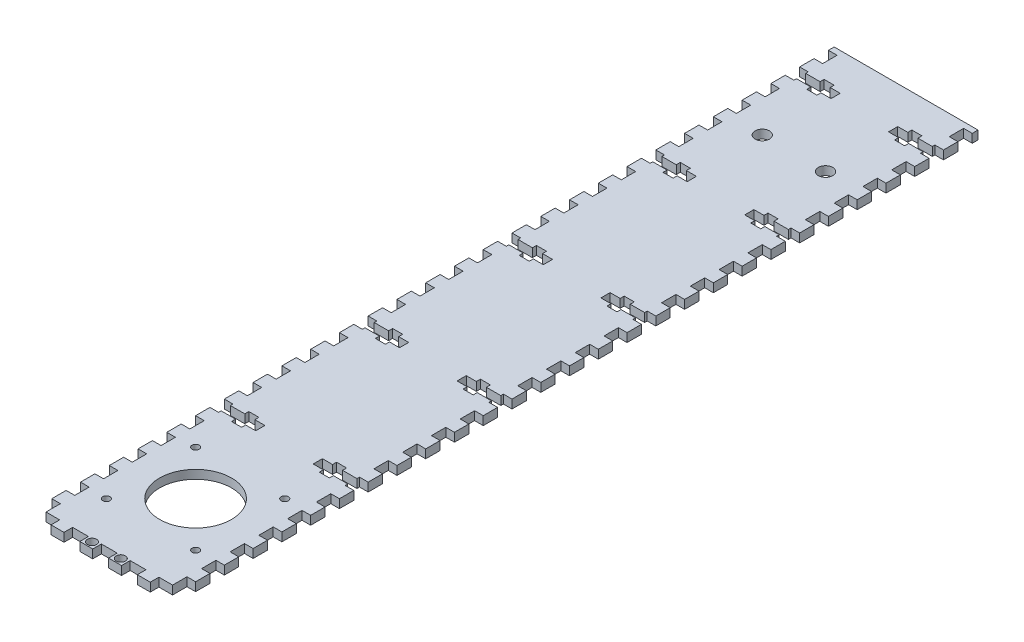
SolidWorks part; units mm, degrees
ref_plane "Plan de face" through (0, 0, 0) normal (0, 0, 1) x (1, 0, 0)
ref_plane "Plan de dessus" through (0, 0, 0) normal (0, 1, 0) x (1, 0, 0)
ref_plane "Plan de droite" through (0, 0, 0) normal (1, 0, 0) x (0, 0, -1)
sketch "Sketch1" plane through (0, 0, 0) normal (0, 0, 1) x (1, 0, 0)
  line L1 (-79.7436, 30.1282) -> (-29.7436, 30.1282)
  line L2 (-79.7436, 30.1282) -> (-79.7436, 27.1282)
  line L3 (-79.7436, 27.1282) -> (-29.7436, 27.1282)
  line L4 (-29.7436, 30.1282) -> (-29.7436, 27.1282)
  dimension "D1" = 50
  dimension "D2" = 3
extrude "Boss-Extrude1" add sketch "Sketch1" along normal blind 277
sketch "Sketch3" plane through (0, 30.1282, 0) normal (0, 1, 0) x (1, 0, 0)
  line L0 (-79.7436, -277) -> (-76.7436, -277)
  line L1 (-29.7436, -277) -> (-79.7436, -277) construction
  line L2 (-29.7436, 0) -> (-79.7436, 0) construction
  line L3 (-54.7436, 0) -> (-54.7436, -277) construction
  line L4 (-29.7436, -277) -> (-32.7436, -277)
  line L5 (-29.7436, -277) -> (-29.7436, -272)
  line L6 (-29.7436, -272) -> (-32.7436, -272)
  line L7 (-32.7436, -277) -> (-32.7436, -272)
  line L8 (-79.7436, -277) -> (-79.7436, -272)
  line L9 (-79.7436, -272) -> (-76.7436, -272)
  line L10 (-76.7436, -277) -> (-76.7436, -272)
  line L11 (-79.7436, -267) -> (-76.7436, -267)
  line L12 (-76.7436, -267) -> (-76.7436, -262)
  line L13 (-79.7436, -262) -> (-76.7436, -262)
  line L14 (-79.7436, -267) -> (-79.7436, -262)
  line L15 (-29.7436, -267) -> (-29.7436, -262)
  line L16 (-29.7436, -267) -> (-32.7436, -267)
  line L17 (-32.7436, -267) -> (-32.7436, -262)
  line L18 (-29.7436, -262) -> (-32.7436, -262)
  line L19 (-79.7436, -257) -> (-76.7436, -257)
  line L20 (-76.7436, -257) -> (-76.7436, -252)
  line L21 (-79.7436, -252) -> (-76.7436, -252)
  line L22 (-79.7436, -257) -> (-79.7436, -252)
  line L23 (-29.7436, -257) -> (-29.7436, -252)
  line L24 (-29.7436, -257) -> (-32.7436, -257)
  line L25 (-32.7436, -257) -> (-32.7436, -252)
  line L26 (-29.7436, -252) -> (-32.7436, -252)
  line L27 (-79.7436, -247) -> (-76.7436, -247)
  line L28 (-76.7436, -247) -> (-76.7436, -242)
  line L29 (-79.7436, -242) -> (-76.7436, -242)
  line L30 (-79.7436, -247) -> (-79.7436, -242)
  line L31 (-29.7436, -247) -> (-29.7436, -242)
  line L32 (-29.7436, -247) -> (-32.7436, -247)
  line L33 (-32.7436, -247) -> (-32.7436, -242)
  line L34 (-29.7436, -242) -> (-32.7436, -242)
  line L35 (-79.7436, -237) -> (-76.7436, -237)
  line L36 (-76.7436, -237) -> (-76.7436, -232)
  line L37 (-79.7436, -232) -> (-76.7436, -232)
  line L38 (-79.7436, -237) -> (-79.7436, -232)
  line L39 (-29.7436, -237) -> (-29.7436, -232)
  line L40 (-29.7436, -237) -> (-32.7436, -237)
  line L41 (-32.7436, -237) -> (-32.7436, -232)
  line L42 (-29.7436, -232) -> (-32.7436, -232)
  line L43 (-79.7436, -227) -> (-76.7436, -227)
  line L44 (-76.7436, -227) -> (-76.7436, -222)
  line L45 (-79.7436, -222) -> (-76.7436, -222)
  line L46 (-79.7436, -227) -> (-79.7436, -222)
  line L47 (-29.7436, -227) -> (-29.7436, -222)
  line L48 (-29.7436, -227) -> (-32.7436, -227)
  line L49 (-32.7436, -227) -> (-32.7436, -222)
  line L50 (-29.7436, -222) -> (-32.7436, -222)
  line L51 (-79.7436, -217) -> (-76.7436, -217)
  line L52 (-76.7436, -217) -> (-76.7436, -212)
  line L53 (-79.7436, -212) -> (-76.7436, -212)
  line L54 (-79.7436, -217) -> (-79.7436, -212)
  line L55 (-29.7436, -217) -> (-29.7436, -212)
  line L56 (-29.7436, -217) -> (-32.7436, -217)
  line L57 (-32.7436, -217) -> (-32.7436, -212)
  line L58 (-29.7436, -212) -> (-32.7436, -212)
  line L59 (-79.7436, -207) -> (-76.7436, -207)
  line L60 (-76.7436, -207) -> (-76.7436, -202)
  line L61 (-79.7436, -202) -> (-76.7436, -202)
  line L62 (-79.7436, -207) -> (-79.7436, -202)
  line L63 (-29.7436, -207) -> (-29.7436, -202)
  line L64 (-29.7436, -207) -> (-32.7436, -207)
  line L65 (-32.7436, -207) -> (-32.7436, -202)
  line L66 (-29.7436, -202) -> (-32.7436, -202)
  line L67 (-79.7436, -197) -> (-76.7436, -197)
  line L68 (-76.7436, -197) -> (-76.7436, -192)
  line L69 (-79.7436, -192) -> (-76.7436, -192)
  line L70 (-79.7436, -197) -> (-79.7436, -192)
  line L71 (-29.7436, -197) -> (-29.7436, -192)
  line L72 (-29.7436, -197) -> (-32.7436, -197)
  line L73 (-32.7436, -197) -> (-32.7436, -192)
  line L74 (-29.7436, -192) -> (-32.7436, -192)
  line L75 (-79.7436, -187) -> (-76.7436, -187)
  line L76 (-76.7436, -187) -> (-76.7436, -182)
  line L77 (-79.7436, -182) -> (-76.7436, -182)
  line L78 (-79.7436, -187) -> (-79.7436, -182)
  line L79 (-29.7436, -187) -> (-29.7436, -182)
  line L80 (-29.7436, -187) -> (-32.7436, -187)
  line L81 (-32.7436, -187) -> (-32.7436, -182)
  line L82 (-29.7436, -182) -> (-32.7436, -182)
  line L83 (-79.7436, -177) -> (-76.7436, -177)
  line L84 (-76.7436, -177) -> (-76.7436, -172)
  line L85 (-79.7436, -172) -> (-76.7436, -172)
  line L86 (-79.7436, -177) -> (-79.7436, -172)
  line L87 (-29.7436, -177) -> (-29.7436, -172)
  line L88 (-29.7436, -177) -> (-32.7436, -177)
  line L89 (-32.7436, -177) -> (-32.7436, -172)
  line L90 (-29.7436, -172) -> (-32.7436, -172)
  line L91 (-79.7436, -167) -> (-76.7436, -167)
  line L92 (-76.7436, -167) -> (-76.7436, -162)
  line L93 (-79.7436, -162) -> (-76.7436, -162)
  line L94 (-79.7436, -167) -> (-79.7436, -162)
  line L95 (-29.7436, -167) -> (-29.7436, -162)
  line L96 (-29.7436, -167) -> (-32.7436, -167)
  line L97 (-32.7436, -167) -> (-32.7436, -162)
  line L98 (-29.7436, -162) -> (-32.7436, -162)
  line L99 (-79.7436, -157) -> (-76.7436, -157)
  line L100 (-76.7436, -157) -> (-76.7436, -152)
  line L101 (-79.7436, -152) -> (-76.7436, -152)
  line L102 (-79.7436, -157) -> (-79.7436, -152)
  line L103 (-29.7436, -157) -> (-29.7436, -152)
  line L104 (-29.7436, -157) -> (-32.7436, -157)
  line L105 (-32.7436, -157) -> (-32.7436, -152)
  line L106 (-29.7436, -152) -> (-32.7436, -152)
  line L107 (-79.7436, -147) -> (-76.7436, -147)
  line L108 (-76.7436, -147) -> (-76.7436, -142)
  line L109 (-79.7436, -142) -> (-76.7436, -142)
  line L110 (-79.7436, -147) -> (-79.7436, -142)
  line L111 (-29.7436, -147) -> (-29.7436, -142)
  line L112 (-29.7436, -147) -> (-32.7436, -147)
  line L113 (-32.7436, -147) -> (-32.7436, -142)
  line L114 (-29.7436, -142) -> (-32.7436, -142)
  line L115 (-79.7436, -137) -> (-76.7436, -137)
  line L116 (-76.7436, -137) -> (-76.7436, -132)
  line L117 (-79.7436, -132) -> (-76.7436, -132)
  line L118 (-79.7436, -137) -> (-79.7436, -132)
  line L119 (-29.7436, -137) -> (-29.7436, -132)
  line L120 (-29.7436, -137) -> (-32.7436, -137)
  line L121 (-32.7436, -137) -> (-32.7436, -132)
  line L122 (-29.7436, -132) -> (-32.7436, -132)
  line L123 (-79.7436, -127) -> (-76.7436, -127)
  line L124 (-76.7436, -127) -> (-76.7436, -122)
  line L125 (-79.7436, -122) -> (-76.7436, -122)
  line L126 (-79.7436, -127) -> (-79.7436, -122)
  line L127 (-29.7436, -127) -> (-29.7436, -122)
  line L128 (-29.7436, -127) -> (-32.7436, -127)
  line L129 (-32.7436, -127) -> (-32.7436, -122)
  line L130 (-29.7436, -122) -> (-32.7436, -122)
  line L131 (-79.7436, -117) -> (-76.7436, -117)
  line L132 (-76.7436, -117) -> (-76.7436, -112)
  line L133 (-79.7436, -112) -> (-76.7436, -112)
  line L134 (-79.7436, -117) -> (-79.7436, -112)
  line L135 (-29.7436, -117) -> (-29.7436, -112)
  line L136 (-29.7436, -117) -> (-32.7436, -117)
  line L137 (-32.7436, -117) -> (-32.7436, -112)
  line L138 (-29.7436, -112) -> (-32.7436, -112)
  line L139 (-79.7436, -107) -> (-76.7436, -107)
  line L140 (-76.7436, -107) -> (-76.7436, -102)
  line L141 (-79.7436, -102) -> (-76.7436, -102)
  line L142 (-79.7436, -107) -> (-79.7436, -102)
  line L143 (-29.7436, -107) -> (-29.7436, -102)
  line L144 (-29.7436, -107) -> (-32.7436, -107)
  line L145 (-32.7436, -107) -> (-32.7436, -102)
  line L146 (-29.7436, -102) -> (-32.7436, -102)
  line L147 (-79.7436, -97) -> (-76.7436, -97)
  line L148 (-76.7436, -97) -> (-76.7436, -92)
  line L149 (-79.7436, -92) -> (-76.7436, -92)
  line L150 (-79.7436, -97) -> (-79.7436, -92)
  line L151 (-29.7436, -97) -> (-29.7436, -92)
  line L152 (-29.7436, -97) -> (-32.7436, -97)
  line L153 (-32.7436, -97) -> (-32.7436, -92)
  line L154 (-29.7436, -92) -> (-32.7436, -92)
  line L155 (-79.7436, -87) -> (-76.7436, -87)
  line L156 (-76.7436, -87) -> (-76.7436, -82)
  line L157 (-79.7436, -82) -> (-76.7436, -82)
  line L158 (-79.7436, -87) -> (-79.7436, -82)
  line L159 (-29.7436, -87) -> (-29.7436, -82)
  line L160 (-29.7436, -87) -> (-32.7436, -87)
  line L161 (-32.7436, -87) -> (-32.7436, -82)
  line L162 (-29.7436, -82) -> (-32.7436, -82)
  line L163 (-79.7436, -77) -> (-76.7436, -77)
  line L164 (-76.7436, -77) -> (-76.7436, -72)
  line L165 (-79.7436, -72) -> (-76.7436, -72)
  line L166 (-79.7436, -77) -> (-79.7436, -72)
  line L167 (-29.7436, -77) -> (-29.7436, -72)
  line L168 (-29.7436, -77) -> (-32.7436, -77)
  line L169 (-32.7436, -77) -> (-32.7436, -72)
  line L170 (-29.7436, -72) -> (-32.7436, -72)
  line L171 (-79.7436, -67) -> (-76.7436, -67)
  line L172 (-76.7436, -67) -> (-76.7436, -62)
  line L173 (-79.7436, -62) -> (-76.7436, -62)
  line L174 (-79.7436, -67) -> (-79.7436, -62)
  line L175 (-29.7436, -67) -> (-29.7436, -62)
  line L176 (-29.7436, -67) -> (-32.7436, -67)
  line L177 (-32.7436, -67) -> (-32.7436, -62)
  line L178 (-29.7436, -62) -> (-32.7436, -62)
  line L179 (-79.7436, -57) -> (-76.7436, -57)
  line L180 (-76.7436, -57) -> (-76.7436, -52)
  line L181 (-79.7436, -52) -> (-76.7436, -52)
  line L182 (-79.7436, -57) -> (-79.7436, -52)
  line L183 (-29.7436, -57) -> (-29.7436, -52)
  line L184 (-29.7436, -57) -> (-32.7436, -57)
  line L185 (-32.7436, -57) -> (-32.7436, -52)
  line L186 (-29.7436, -52) -> (-32.7436, -52)
  line L187 (-79.7436, -47) -> (-76.7436, -47)
  line L188 (-76.7436, -47) -> (-76.7436, -42)
  line L189 (-79.7436, -42) -> (-76.7436, -42)
  line L190 (-79.7436, -47) -> (-79.7436, -42)
  line L191 (-29.7436, -47) -> (-29.7436, -42)
  line L192 (-29.7436, -47) -> (-32.7436, -47)
  line L193 (-32.7436, -47) -> (-32.7436, -42)
  line L194 (-29.7436, -42) -> (-32.7436, -42)
  line L195 (-79.7436, -37) -> (-76.7436, -37)
  line L196 (-76.7436, -37) -> (-76.7436, -32)
  line L197 (-79.7436, -32) -> (-76.7436, -32)
  line L198 (-79.7436, -37) -> (-79.7436, -32)
  line L199 (-29.7436, -37) -> (-29.7436, -32)
  line L200 (-29.7436, -37) -> (-32.7436, -37)
  line L201 (-32.7436, -37) -> (-32.7436, -32)
  line L202 (-29.7436, -32) -> (-32.7436, -32)
  line L203 (-79.7436, -27) -> (-76.7436, -27)
  line L204 (-76.7436, -27) -> (-76.7436, -22)
  line L205 (-79.7436, -22) -> (-76.7436, -22)
  line L206 (-79.7436, -27) -> (-79.7436, -22)
  line L207 (-29.7436, -27) -> (-29.7436, -22)
  line L208 (-29.7436, -27) -> (-32.7436, -27)
  line L209 (-32.7436, -27) -> (-32.7436, -22)
  line L210 (-29.7436, -22) -> (-32.7436, -22)
  line L211 (-79.7436, -17) -> (-76.7436, -17)
  line L212 (-76.7436, -17) -> (-76.7436, -12)
  line L213 (-79.7436, -12) -> (-76.7436, -12)
  line L214 (-79.7436, -17) -> (-79.7436, -12)
  line L215 (-29.7436, -17) -> (-29.7436, -12)
  line L216 (-29.7436, -17) -> (-32.7436, -17)
  line L217 (-32.7436, -17) -> (-32.7436, -12)
  line L218 (-29.7436, -12) -> (-32.7436, -12)
  line L219 (-79.7436, -7) -> (-76.7436, -7)
  line L220 (-76.7436, -7) -> (-76.7436, -2)
  line L221 (-79.7436, -2) -> (-76.7436, -2)
  line L222 (-79.7436, -7) -> (-79.7436, -2)
  line L223 (-29.7436, -7) -> (-29.7436, -2)
  line L224 (-29.7436, -7) -> (-32.7436, -7)
  line L225 (-32.7436, -7) -> (-32.7436, -2)
  line L226 (-29.7436, -2) -> (-32.7436, -2)
  dimension "D1" = 3
  dimension "D2" = 5
  dimension "D3" = 28
extrude "Cut-Extrude1" cut sketch "Sketch3" against normal blind 3
sketch "Sketch6" plane through (0, 0, 277) normal (0, 0, 1) x (1, 0, 0)
  line L0 (-32.7436, 30.1282) -> (-76.7436, 30.1282) construction
  line L1 (-71.9936, 30.1282) -> (-67.4936, 30.1282)
  line L2 (-71.9936, 30.1282) -> (-71.9936, 27.1282)
  line L3 (-71.9936, 27.1282) -> (-67.4936, 27.1282)
  line L4 (-67.4936, 30.1282) -> (-67.4936, 27.1282)
  line L5 (-76.7436, 27.1282) -> (-32.7436, 27.1282) construction
  line L6 (-76.7436, 27.1282) -> (-76.7436, 30.1282) construction
  line L7 (-61.9936, 30.1282) -> (-61.9936, 27.1282)
  line L8 (-61.9936, 30.1282) -> (-57.4936, 30.1282)
  line L9 (-57.4936, 30.1282) -> (-57.4936, 27.1282)
  line L10 (-61.9936, 27.1282) -> (-57.4936, 27.1282)
  line L11 (-51.9936, 30.1282) -> (-51.9936, 27.1282)
  line L12 (-51.9936, 30.1282) -> (-47.4936, 30.1282)
  line L13 (-47.4936, 30.1282) -> (-47.4936, 27.1282)
  line L14 (-51.9936, 27.1282) -> (-47.4936, 27.1282)
  line L15 (-41.9936, 30.1282) -> (-41.9936, 27.1282)
  line L16 (-41.9936, 30.1282) -> (-37.4936, 30.1282)
  line L17 (-37.4936, 30.1282) -> (-37.4936, 27.1282)
  line L18 (-41.9936, 27.1282) -> (-37.4936, 27.1282)
  line L20 (-32.7436, 27.1282) -> (-32.7436, 30.1282) construction
  dimension "D1" = 4.75
  dimension "D2" = 4.5
  dimension "D4" = 4.75
  dimension "D3" = 4
extrude "Boss-Extrude2" add sketch "Sketch6" along normal blind 3
sketch "Sketch9" plane through (-32.7436, 0, 0) normal (1, 0, 0) x (0, 0, -1)
  line L0 (-267, 27.1282) -> (-262, 30.1282) construction
  line L1 (-262, 27.1282) -> (-267, 27.1282) construction
  line L2 (-262.9, 30.1282) -> (-266.1, 30.1282)
  line L3 (-262.9, 30.1282) -> (-262.9, 27.1282)
  line L4 (-262.9, 27.1282) -> (-266.1, 27.1282)
  line L5 (-266.1, 30.1282) -> (-266.1, 27.1282)
  line L6 (-262.9, 30.1282) -> (-266.1, 27.1282) construction
  line L7 (-262.9, 27.1282) -> (-266.1, 30.1282) construction
  line L8 (-212.9, 30.1282) -> (-212.9, 27.1282)
  line L9 (-212.9, 30.1282) -> (-216.1, 30.1282)
  line L10 (-216.1, 30.1282) -> (-216.1, 27.1282)
  line L11 (-212.9, 27.1282) -> (-216.1, 27.1282)
  line L12 (-162.9, 30.1282) -> (-162.9, 27.1282)
  line L13 (-162.9, 30.1282) -> (-166.1, 30.1282)
  line L14 (-166.1, 30.1282) -> (-166.1, 27.1282)
  line L15 (-162.9, 27.1282) -> (-166.1, 27.1282)
  line L16 (-112.9, 30.1282) -> (-112.9, 27.1282)
  line L17 (-112.9, 30.1282) -> (-116.1, 30.1282)
  line L18 (-116.1, 30.1282) -> (-116.1, 27.1282)
  line L19 (-112.9, 27.1282) -> (-116.1, 27.1282)
  line L20 (-62.9, 30.1282) -> (-62.9, 27.1282)
  line L21 (-62.9, 30.1282) -> (-66.1, 30.1282)
  line L22 (-66.1, 30.1282) -> (-66.1, 27.1282)
  line L23 (-62.9, 27.1282) -> (-66.1, 27.1282)
  line L24 (-12.9, 30.1282) -> (-12.9, 27.1282)
  line L25 (-12.9, 30.1282) -> (-16.1, 30.1282)
  line L26 (-16.1, 30.1282) -> (-16.1, 27.1282)
  line L27 (-12.9, 27.1282) -> (-16.1, 27.1282)
  point P4 (-264.5, 28.6282)
  dimension "D1" = 3.2
  dimension "D2" = 6
extrude "Cut-Extrude2" cut sketch "Sketch9" against normal blind 12
sketch "Sketch10" plane through (-76.7436, 0, 0) normal (-1, 0, 0) x (0, 0, 1)
  line L0 (267, 30.1282) -> (262, 27.1282) construction
  line L1 (267, 30.1282) -> (262, 30.1282) construction
  line L2 (262.9, 27.1282) -> (266.1, 27.1282)
  line L3 (262.9, 27.1282) -> (262.9, 30.1282)
  line L4 (262.9, 30.1282) -> (266.1, 30.1282)
  line L5 (266.1, 27.1282) -> (266.1, 30.1282)
  line L6 (262.9, 27.1282) -> (266.1, 30.1282) construction
  line L7 (262.9, 30.1282) -> (266.1, 27.1282) construction
  line L8 (212.9, 27.1282) -> (212.9, 30.1282)
  line L9 (212.9, 27.1282) -> (216.1, 27.1282)
  line L10 (216.1, 27.1282) -> (216.1, 30.1282)
  line L11 (212.9, 30.1282) -> (216.1, 30.1282)
  line L12 (162.9, 27.1282) -> (162.9, 30.1282)
  line L13 (162.9, 27.1282) -> (166.1, 27.1282)
  line L14 (166.1, 27.1282) -> (166.1, 30.1282)
  line L15 (162.9, 30.1282) -> (166.1, 30.1282)
  line L16 (112.9, 27.1282) -> (112.9, 30.1282)
  line L17 (112.9, 27.1282) -> (116.1, 27.1282)
  line L18 (116.1, 27.1282) -> (116.1, 30.1282)
  line L19 (112.9, 30.1282) -> (116.1, 30.1282)
  line L20 (62.9, 27.1282) -> (62.9, 30.1282)
  line L21 (62.9, 27.1282) -> (66.1, 27.1282)
  line L22 (66.1, 27.1282) -> (66.1, 30.1282)
  line L23 (62.9, 30.1282) -> (66.1, 30.1282)
  line L24 (12.9, 27.1282) -> (12.9, 30.1282)
  line L25 (12.9, 27.1282) -> (16.1, 27.1282)
  line L26 (16.1, 27.1282) -> (16.1, 30.1282)
  line L27 (12.9, 30.1282) -> (16.1, 30.1282)
  point P4 (264.5, 28.6282)
  dimension "D1" = 3.2
  dimension "D2" = 6
extrude "Cut-Extrude3" cut sketch "Sketch10" against normal blind 12
sketch "Sketch11" plane through (0, 27.1282, 0) normal (0, -1, 0) x (1, 0, 0)
  line L0 (-54.7436, 277) -> (-54.7436, 0) construction
  line L1 (-71.7436, 267.5) -> (-68.2436, 267.5)
  line L2 (-71.7436, 267.5) -> (-71.7436, 261.5)
  line L3 (-71.7436, 261.5) -> (-68.2436, 261.5)
  line L4 (-68.2436, 267.5) -> (-68.2436, 261.5)
  line L5 (-57.4936, 277) -> (-51.9936, 277) construction
  line L6 (-79.7436, 0) -> (-29.7436, 0) construction
  line L8 (-76.7436, 267) -> (-76.7436, 266.1) construction
  line L9 (-37.7436, 261.5) -> (-41.2436, 261.5)
  line L10 (-41.2436, 267.5) -> (-41.2436, 261.5)
  line L11 (-37.7436, 267.5) -> (-41.2436, 267.5)
  line L12 (-37.7436, 267.5) -> (-37.7436, 261.5)
  line L13 (-71.7436, 217.5) -> (-71.7436, 211.5)
  line L14 (-71.7436, 217.5) -> (-68.2436, 217.5)
  line L15 (-68.2436, 217.5) -> (-68.2436, 211.5)
  line L16 (-71.7436, 211.5) -> (-68.2436, 211.5)
  line L17 (-37.7436, 211.5) -> (-41.2436, 211.5)
  line L18 (-41.2436, 217.5) -> (-41.2436, 211.5)
  line L19 (-37.7436, 217.5) -> (-41.2436, 217.5)
  line L20 (-37.7436, 217.5) -> (-37.7436, 211.5)
  line L21 (-71.7436, 167.5) -> (-71.7436, 161.5)
  line L22 (-71.7436, 167.5) -> (-68.2436, 167.5)
  line L23 (-68.2436, 167.5) -> (-68.2436, 161.5)
  line L24 (-71.7436, 161.5) -> (-68.2436, 161.5)
  line L25 (-37.7436, 161.5) -> (-41.2436, 161.5)
  line L26 (-41.2436, 167.5) -> (-41.2436, 161.5)
  line L27 (-37.7436, 167.5) -> (-41.2436, 167.5)
  line L28 (-37.7436, 167.5) -> (-37.7436, 161.5)
  line L29 (-71.7436, 117.5) -> (-71.7436, 111.5)
  line L30 (-71.7436, 117.5) -> (-68.2436, 117.5)
  line L31 (-68.2436, 117.5) -> (-68.2436, 111.5)
  line L32 (-71.7436, 111.5) -> (-68.2436, 111.5)
  line L33 (-37.7436, 111.5) -> (-41.2436, 111.5)
  line L34 (-41.2436, 117.5) -> (-41.2436, 111.5)
  line L35 (-37.7436, 117.5) -> (-41.2436, 117.5)
  line L36 (-37.7436, 117.5) -> (-37.7436, 111.5)
  line L37 (-71.7436, 67.5) -> (-71.7436, 61.5)
  line L38 (-71.7436, 67.5) -> (-68.2436, 67.5)
  line L39 (-68.2436, 67.5) -> (-68.2436, 61.5)
  line L40 (-71.7436, 61.5) -> (-68.2436, 61.5)
  line L41 (-37.7436, 61.5) -> (-41.2436, 61.5)
  line L42 (-41.2436, 67.5) -> (-41.2436, 61.5)
  line L43 (-37.7436, 67.5) -> (-41.2436, 67.5)
  line L44 (-37.7436, 67.5) -> (-37.7436, 61.5)
  line L45 (-71.7436, 17.5) -> (-71.7436, 11.5)
  line L46 (-71.7436, 17.5) -> (-68.2436, 17.5)
  line L47 (-68.2436, 17.5) -> (-68.2436, 11.5)
  line L48 (-71.7436, 11.5) -> (-68.2436, 11.5)
  line L49 (-37.7436, 11.5) -> (-41.2436, 11.5)
  line L50 (-41.2436, 17.5) -> (-41.2436, 11.5)
  line L51 (-37.7436, 17.5) -> (-41.2436, 17.5)
  line L52 (-37.7436, 17.5) -> (-37.7436, 11.5)
  line L54 (-64.7436, 262.9) -> (-76.7436, 262.9) construction
  dimension "D1" = 6
  dimension "D2" = 1.4
  dimension "D3" = 5
  dimension "D4" = 3.5
  dimension "D5" = 6
extrude "Cut-Extrude4" cut sketch "Sketch11" against normal blind 12
sketch "Sketch12" plane through (0, 27.1282, 0) normal (0, -1, 0) x (1, 0, 0)
  line L0 (-61.9936, 280) -> (-57.4936, 280) construction
  line L1 (-51.9936, 280) -> (-47.4936, 280) construction
  circle A0 centre (-59.7436, 278) radius 1.6
  circle A1 centre (-49.7436, 278) radius 1.6
  dimension "D1" = 3.2
  dimension "D2" = 3.2
  dimension "D3" = 2
  dimension "D4" = 2
extrude "Cut-Extrude5" cut sketch "Sketch12" against normal blind 12
sketch "Sketch13" plane through (0, 27.1282, 0) normal (0, -1, 0) x (1, 0, 0)
  line L1 (-76.7436, 268.1148) -> (-62.8838, 268.1148)
  line L2 (-76.7436, 268.1148) -> (-76.7436, 260.8187)
  line L3 (-76.7436, 260.8187) -> (-62.8838, 260.8187)
  line L4 (-62.8838, 268.1148) -> (-62.8838, 260.8187)
  line L5 (-45.3031, 267.5927) -> (-32.6584, 267.5927)
  line L6 (-45.3031, 267.5927) -> (-45.3031, 260.3726)
  line L7 (-45.3031, 260.3726) -> (-32.6584, 260.3726)
  line L8 (-32.6584, 267.5927) -> (-32.6584, 260.3726)
  point P10 (-62.9061, 267)
  point P11 (-62.9692, 268.1148)
  point P12 (-62.8838, 260.8187)
  point P13 (-45.3031, 261.0613)
  point P14 (-32.6584, 260.3726)
extrude "Boss-Extrude3" add sketch "Sketch13" against normal blind 3
sketch "Sketch14" plane through (0, 27.1282, 0) normal (0, -1, 0) x (1, 0, 0)
  line L0 (-70.2436, 262.5) -> (-39.2436, 262.5) construction
  line L1 (-70.2436, 262.5) -> (-70.2436, 231.5) construction
  line L2 (-70.2436, 231.5) -> (-39.2436, 231.5) construction
  line L3 (-39.2436, 262.5) -> (-39.2436, 231.5) construction
  line L5 (-57.4936, 277) -> (-51.9936, 277) construction
  line L6 (-79.7436, 262) -> (-79.7436, 257) construction
  line L7 (-29.7436, 262) -> (-29.7436, 257) construction
  circle A0 centre (-70.2436, 262.5) radius 1.25
  circle A1 centre (-39.2436, 262.5) radius 1.25
  circle A2 centre (-39.2436, 231.5) radius 1.25
  circle A3 centre (-70.2436, 231.5) radius 1.25
  circle A4 centre (-54.7436, 247) radius 12.5
  point P15 (-54.7436, 262.5)
  point P17 (-70.2436, 247)
  dimension "D5" = 25
  dimension "D1" = 31
  dimension "D2" = 31
  dimension "D3" = 30
  dimension "D4" = 25
  dimension "D6" = 25
extrude "Cut-Extrude6" cut sketch "Sketch14" against normal through all both and the other way through all
sketch "Sketch15" plane through (0, 27.1282, 0) normal (0, -1, 0) x (1, 0, 0)
  line L0 (-54.7436, 0) -> (-54.7436, 66.6112) construction
  line L1 (-79.7436, 0) -> (-29.7436, 0) construction
  circle A0 centre (-65.7436, 39) radius 2.5
  circle A1 centre (-43.7436, 39) radius 2.5
  point P9 (-54.7436, 0)
  dimension "D1" = 5
  dimension "D2" = 11
  dimension "D3" = 39
extrude "Cut-Extrude7" cut sketch "Sketch15" against normal through all
